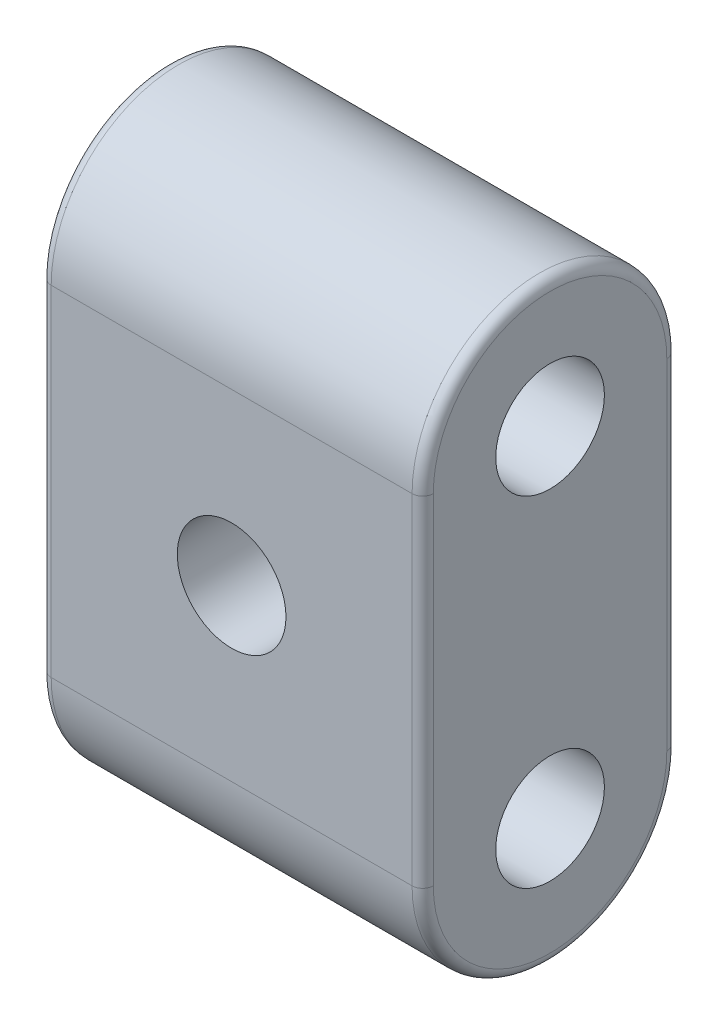
SolidWorks part; units mm, degrees
ref_plane "Front Plane" through (0, 0, 0) normal (0, 0, 1) x (1, 0, 0)
ref_plane "Top Plane" through (0, 0, 0) normal (0, 1, 0) x (1, 0, 0)
ref_plane "Right Plane" through (0, 0, 0) normal (1, 0, 0) x (0, 0, -1)
sketch "Sketch1" plane through (0, 0, 0) normal (1, 0, 0) x (0, 0, -1)
  line L0 (0, 0) -> (0, 12.7) construction
  line L1 (-4.7625, 0) -> (-4.7625, 12.7)
  line L2 (4.7625, 0) -> (4.7625, 12.7)
  arc A0 (-4.7625, 0) -> (4.7625, 0) centre (0, 0) ccw
  arc A1 (4.7625, 12.7) -> (-4.7625, 12.7) centre (0, 12.7) ccw
  circle A2 centre (0, 12.7) radius 2.032
  circle A3 centre (0, 0) radius 2.032
  point P3 (0, 6.35)
  dimension "D1" = 4.7625
  dimension "D2" = 4.064
  dimension "D3" = 12.7
extrude "Boss-Extrude1" add sketch "Sketch1" along normal mid plane 14.2875
sketch "Sketch2" plane through (0, 0, 4.7625) normal (0, 0, 1) x (1, 0, 0)
  line L0 (7.1437, 12.7) -> (7.1437, 0) construction
  circle A0 centre (0, 6.35) radius 2.032
  point P4 (7.1438, 6.35)
  dimension "D1" = 4.064
extrude "Cut-Extrude1" cut sketch "Sketch2" against normal through all
fillet "Fillet1" radius 0.3969 8 edges at (-7.1437, 6.35, -4.7625) (-7.1437, -4.7625, 0) (-7.1437, 6.35, 4.7625) (7.1437, 6.35, -4.7625) (7.1437, -4.7625, 0) (7.1437, 6.35, 4.7625) (-7.1437, 17.4625, 0) (7.1437, 17.4625, 0)
